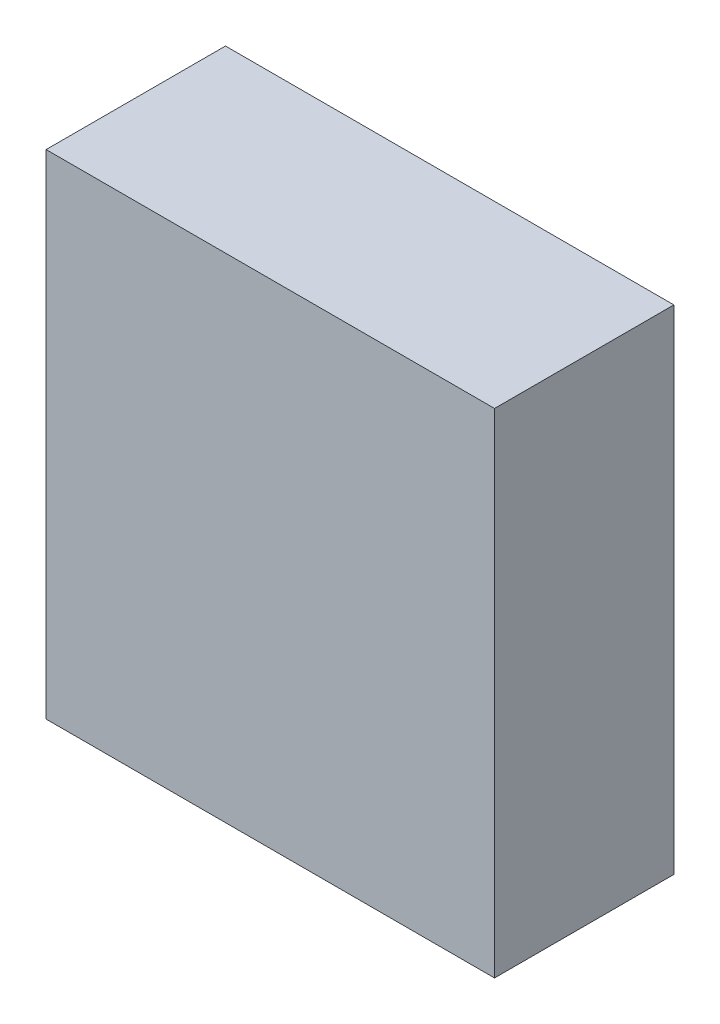
SolidWorks part; units mm, degrees
ref_plane "Front Plane" through (0, 0, 0) normal (0, 0, 1) x (1, 0, 0)
ref_plane "Top Plane" through (0, 0, 0) normal (0, 1, 0) x (1, 0, 0)
ref_plane "Right Plane" through (0, 0, 0) normal (1, 0, 0) x (0, 0, -1)
other "Configuration Table"
sketch "Sketch1" plane through (0, 0, 0) normal (0, 0, 1) x (1, 0, 0)
  line L1 (120, 560) -> (220, 560)
  line L2 (120, 560) -> (120, 670)
  line L3 (120, 670) -> (220, 670)
  line L4 (220, 560) -> (220, 670)
extrude "TOPPING_arka_duvar_pano_plc_1" add sketch "Sketch1" against normal blind 40 from offset 736 separate body
